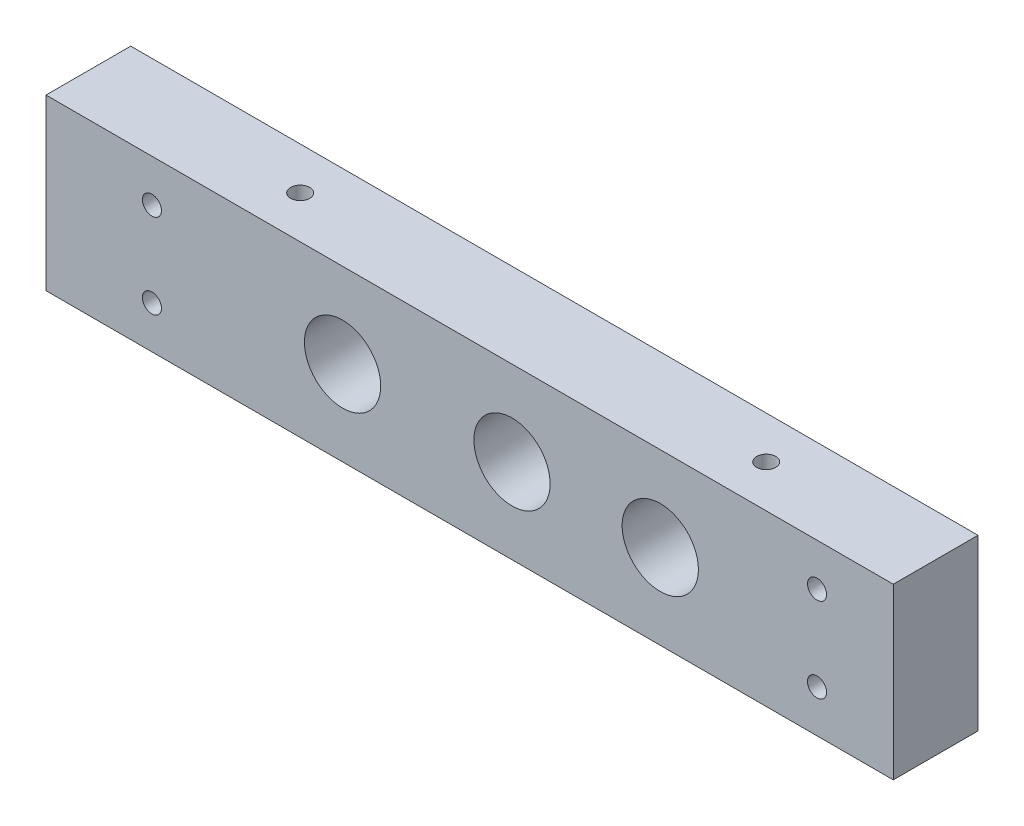
SolidWorks part; units mm, degrees
ref_plane "前视基准面" through (0, 0, 0) normal (0, 0, 1) x (1, 0, 0)
ref_plane "上视基准面" through (0, 0, 0) normal (0, 1, 0) x (1, 0, 0)
ref_plane "右视基准面" through (0, 0, 0) normal (1, 0, 0) x (0, 0, -1)
other "Configuration Table"
sketch "草图1" plane through (0, 0, 0) normal (0, 0, 1) x (1, 0, 0)
  line L1 (0, -20) -> (200, -20)
  line L2 (0, -20) -> (0, 20)
  line L3 (0, 20) -> (200, 20)
  line L4 (200, -20) -> (200, 20)
extrude "前臂200x40x20" add sketch "草图1" along normal blind 20 from offset 10
sketch "草图2" plane through (0, 0, 0) normal (0, 0, 1) x (1, 0, 0)
  circle A0 centre (70, 0) radius 9
  circle A1 centre (110, 0) radius 9
  circle A2 centre (145, 0) radius 9
  circle A3 centre (25, -10) radius 2.25
  circle A4 centre (25, 10) radius 2.25
  circle A5 centre (182, -10) radius 2.25
  circle A6 centre (182, 10) radius 2.25
extrude "减重与拼接相机孔" cut sketch "草图2" against normal through all and the other way through all
sketch "草图3" plane through (0, 0, 0) normal (0, 1, 0) x (1, 0, 0)
  circle A0 centre (50, 0) radius 2.25
  circle A1 centre (160, 0) radius 2.25
extrude "主板托盘竖向M4" cut sketch "草图3" against normal through all and the other way through all
